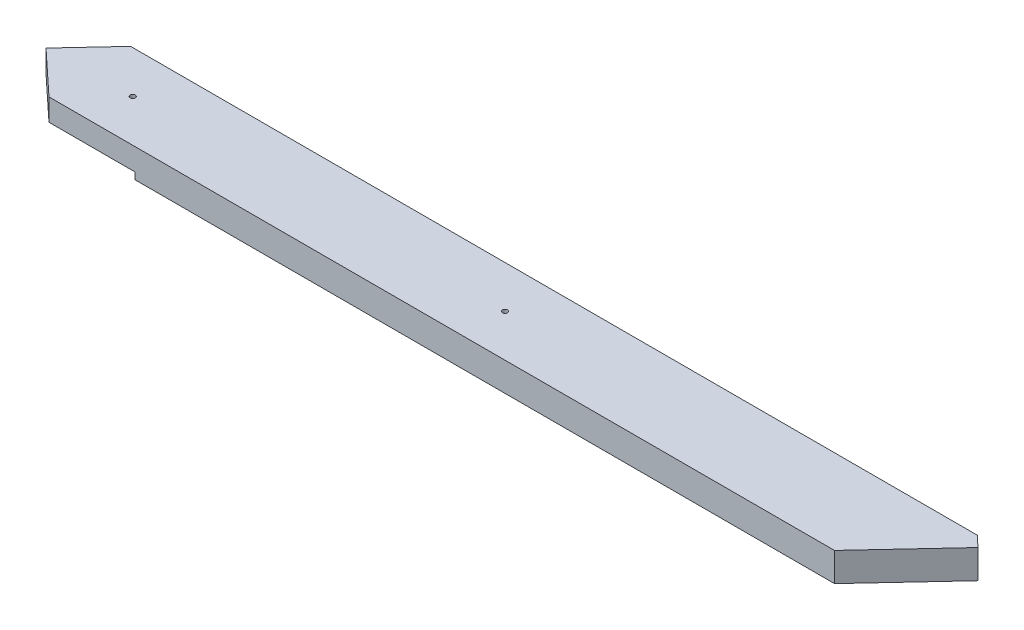
SolidWorks part; units mm, degrees
material "Pine"
ref_plane "Front Plane" through (0, 0, 0) normal (0, 0, 1) x (1, 0, 0)
ref_plane "Top Plane" through (0, 0, 0) normal (0, 1, 0) x (1, 0, 0)
ref_plane "Right Plane" through (0, 0, 0) normal (1, 0, 0) x (0, 0, -1)
sketch "Sketch1" plane through (0, 0, 0) normal (0, 1, 0) x (1, 0, 0)
  line L1 (-550, 50) -> (550, 50)
  line L2 (-550, 50) -> (-550, -50)
  line L3 (-550, -50) -> (550, -50)
  line L4 (550, 50) -> (550, -50)
  line L5 (-550, 50) -> (550, -50) construction
  line L6 (-550, -50) -> (550, 50) construction
  point P0 (0, 0)
  dimension "D1" = 1100
  dimension "D2" = 100
extrude "Boss-Extrude1" add sketch "Sketch1" along normal blind 34
sketch "Sketch2" plane through (0, 0, 0) normal (0, -1, 0) x (1, 0, 0)
  circle A0 centre (0, 0) radius 3
extrude "Cut-Extrude1" cut sketch "Sketch2" against normal through all
pattern_linear "LPattern1" count 2 spacing 440 along (-1, 0, 0) of "Cut-Extrude1"
sketch "Sketch5" plane through (0, 34, 0) normal (0, 1, 0) x (1, 0, 0)
  line L0 (439.5489, -50) -> (521.3671, 37.7826)
  line L1 (-550, -50) -> (550, -50) construction
  line L2 (521.3671, 37.7826) -> (508.2591, 50)
  line L3 (550, 50) -> (-550, 50) construction
  line L4 (508.2591, 50) -> (581.2691, 128.3324)
  line L5 (581.2691, 128.3324) -> (679.928, 36.3768)
  line L6 (679.928, 36.3768) -> (491.2241, -166.0833)
  line L7 (491.2241, -166.0833) -> (439.5489, -50)
  line L8 (-93.0312, -621.4044) -> (588.787, 110.1173) construction
  dimension "D1" = 120
extrude "Cut-Extrude2" cut sketch "Sketch5" against normal through all
sketch "Sketch6" plane through (0, 34, 0) normal (0, 1, 0) x (1, 0, 0)
  line L0 (-489.0217, -50) -> (-540.7626, -1.7747)
  line L1 (-550, -50) -> (439.5489, -50) construction
  line L2 (-540.7626, -1.7747) -> (-492.5057, 50)
  line L3 (508.2591, 50) -> (-550, 50) construction
  line L4 (-492.5057, 50) -> (-536.0548, 101.7987)
  line L5 (-536.0548, 101.7987) -> (-635.2222, -14.4406)
  line L6 (-635.2222, -14.4406) -> (-530.1789, -116.4447)
  line L7 (-530.1789, -116.4447) -> (-489.0217, -50)
  line L8 (-540.7626, -1.7747) -> (-434.692, -100.6383) construction
  line L9 (-540.7626, -1.7747) -> (-36.2171, 539.5513) construction
extrude "Cut-Extrude3" cut sketch "Sketch6" against normal through all
sketch "Sketch7" plane through (0, 0, 0) normal (0, -1, 0) x (1, 0, 0)
  line L0 (-572.786, -266.8245) -> (-122.9993, -233.7762)
  line L1 (-122.9993, -233.7762) -> (-501.9741, 172.8252)
  line L2 (-501.9741, 172.8252) -> (-893.096, 137.1907)
  line L3 (-893.096, 137.1907) -> (-572.786, -266.8245)
  line L4 (-294.2888, -50) -> (-387.4943, 50) construction
extrude "Cut-Extrude4" cut sketch "Sketch7" against normal blind 8
equation "\"noga\"=440"
equation "\"D3@LPattern1\"=\"noga\""
